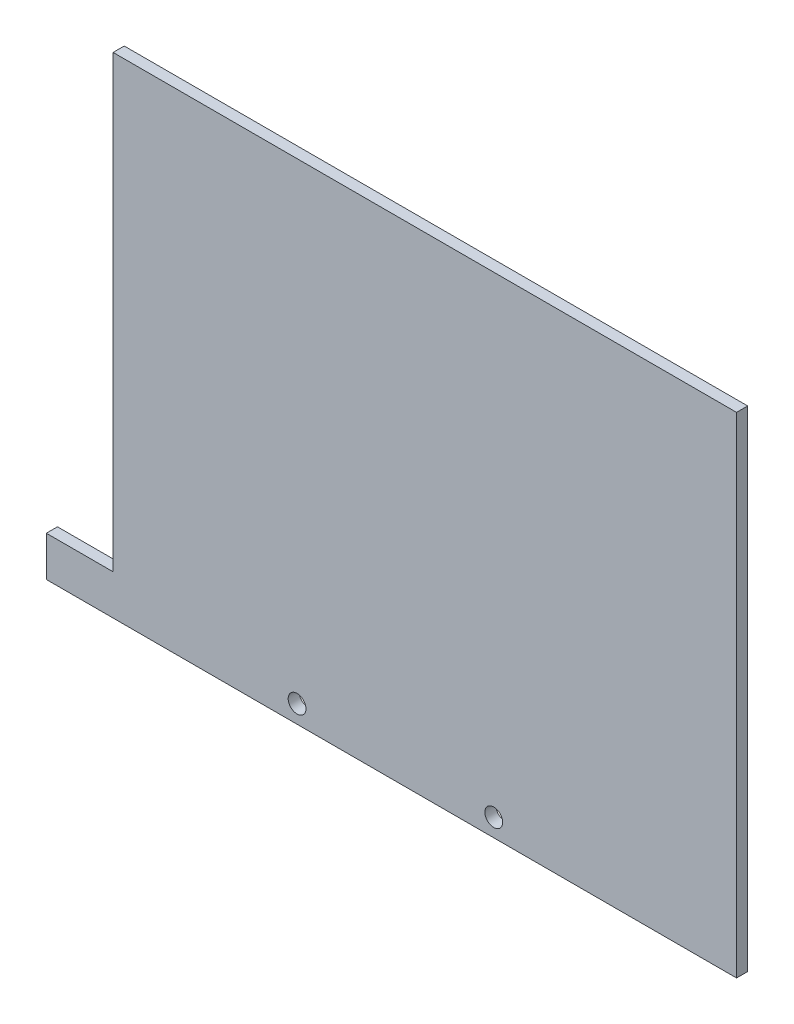
SolidWorks part; units mm, degrees
ref_plane "Front Plane" through (0, 0, 0) normal (0, 0, 1) x (1, 0, 0)
ref_plane "Top Plane" through (0, 0, 0) normal (0, 1, 0) x (1, 0, 0)
ref_plane "Right Plane" through (0, 0, 0) normal (1, 0, 0) x (0, 0, -1)
sketch "Sketch1" plane through (0, 0, 0) normal (0, 0, 1) x (1, 0, 0)
  line L1 (-140, -110) -> (140, -110)
  line L2 (-140, -110) -> (-140, 110)
  line L3 (-140, 110) -> (140, 110)
  line L4 (140, -110) -> (140, 110)
  line L5 (0, 110) -> (0, -110) construction
  line L6 (-140, 0) -> (140, 0) construction
  line L7 (-140, -110) -> (-170, -110)
  line L8 (-140, -110) -> (-140, -92)
  line L9 (-140, -92) -> (-170, -92)
  line L10 (-170, -110) -> (-170, -92)
  point P0 (0, 0)
  dimension "D1" = 220
  dimension "D2" = 280
  dimension "D3" = 18
  dimension "D4" = 30
extrude "Boss-Extrude1" add sketch "Sketch1" along normal blind 5 contours L1 L4 L3 L2 | L10 L7 L2 L9
sketch "Sketch2" plane through (0, 0, 5) normal (0, 0, 1) x (1, 0, 0)
  line L0 (-170, -110) -> (140, -110) construction
  circle A0 centre (-57.3771, -102) radius 4
  circle A1 centre (30.9505, -102) radius 4
  point P4 (-88.3537, -102.4278)
  point P5 (30.9505, -102.4278)
  point P8 (0, 0)
  point P9 (-57.3771, -102)
  dimension "D1" = 8
  dimension "D2" = 8
  dimension "D3" = 8
extrude "Cut-Extrude1" cut sketch "Sketch2" against normal blind 10
